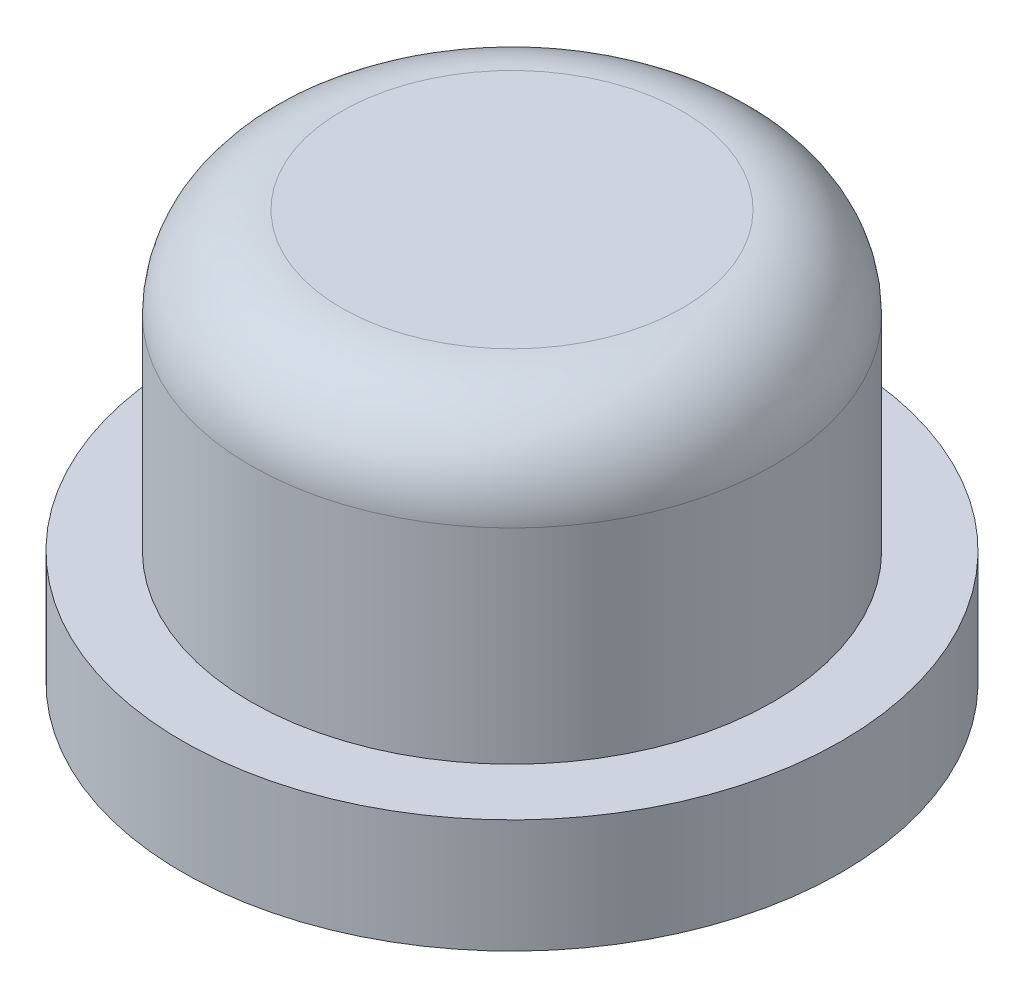
SolidWorks part; units mm, degrees
ref_plane "前视基准面" through (0, 0, 0) normal (0, 0, 1) x (1, 0, 0)
ref_plane "上视基准面" through (0, 0, 0) normal (0, 1, 0) x (1, 0, 0)
ref_plane "右视基准面" through (0, 0, 0) normal (1, 0, 0) x (0, 0, -1)
ref_plane "基准面5" through (0, 0, -3.85) normal (0, 0, 1) x (1, 0, 0)
sketch "草图2" plane through (0, 0, -3.85) normal (0, 0, 1) x (1, 0, 0)
  line L0 (1.5, 3.6) -> (0, 3.6)
  line L1 (0, 3.6) -> (0, 0)
  line L2 (0, 0) -> (2.9, 0)
  line L6 (2.3, 1) -> (2.3, 2.8)
  line L7 (0, 3.6) -> (0, 0) construction
  line L9 (2.3, 1) -> (2.9, 1)
  line L10 (2.9, 1) -> (2.9, 0)
  arc A0 (2.3, 2.8) -> (1.5, 3.6) centre (1.5, 2.8) ccw
  dimension "D1" = 0.8
  dimension "D2" = 2.3
  dimension "D4" = 2.9
  dimension "D6" = 1
  dimension "D7" = 3.6
revolve "旋转1" add sketch "草图2" angle 360 about L7
sketch "草图5" plane through (0, 0, 0) normal (0, -1, 0) x (1, 0, 0)
  circle A0 centre (0, -3.85) radius 2.9 construction
  circle A1 centre (0, -3.85) radius 2.9 construction
  circle A2 centre (0, -3.85) radius 1.8
  dimension "D1" = 3.6
extrude "切除-拉伸1" cut sketch "草图5" against normal blind 2.2
